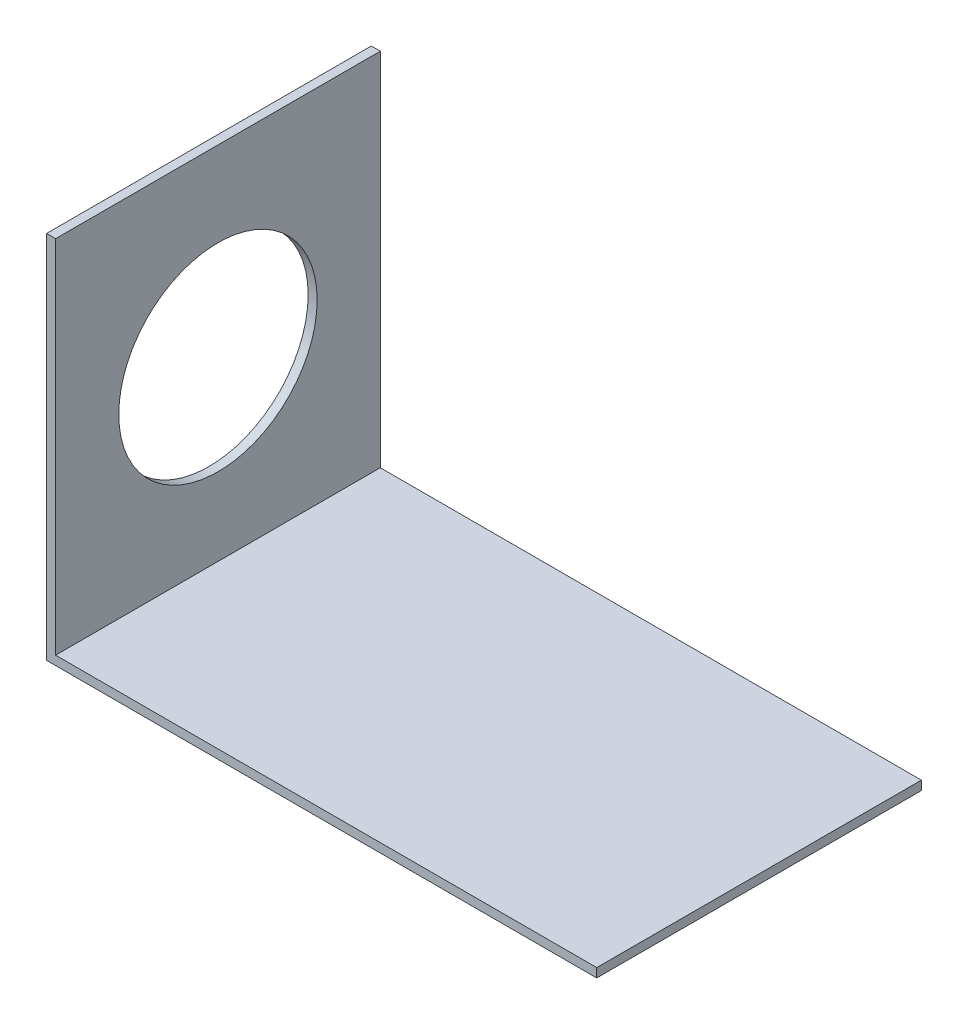
SolidWorks part; units mm, degrees
ref_plane "Front Plane" through (0, 0, 0) normal (0, 0, 1) x (1, 0, 0)
ref_plane "Top Plane" through (0, 0, 0) normal (0, 1, 0) x (1, 0, 0)
ref_plane "Right Plane" through (0, 0, 0) normal (1, 0, 0) x (0, 0, -1)
sketch "Sketch1" plane through (0, 0, 0) normal (0, 0, 1) x (1, 0, 0)
  line L0 (-74.854, 40) -> (-74.854, 0)
  line L1 (-74.854, 0) -> (-14.854, 0)
  line L2 (-75.854, 40) -> (-75.854, -1)
  line L3 (-75.854, -1) -> (-14.854, -1)
  line L4 (-75.854, 40) -> (-74.854, 40)
  line L5 (-14.854, 0) -> (-14.854, -1)
  dimension "D1" = 60
  dimension "D2" = 40
  dimension "D3" = 1
extrude "Boss-Extrude1" add sketch "Sketch1" along normal blind 36
sketch "Sketch2" plane through (-74.854, 0, 0) normal (1, 0, 0) x (0, 0, -1)
  line L2 (-36, 0) -> (0, 0) construction
  circle A0 centre (-18, 19.61) radius 11
  dimension "D1" = 19.61
extrude "Cut-Extrude1" cut sketch "Sketch2" against normal blind 40
